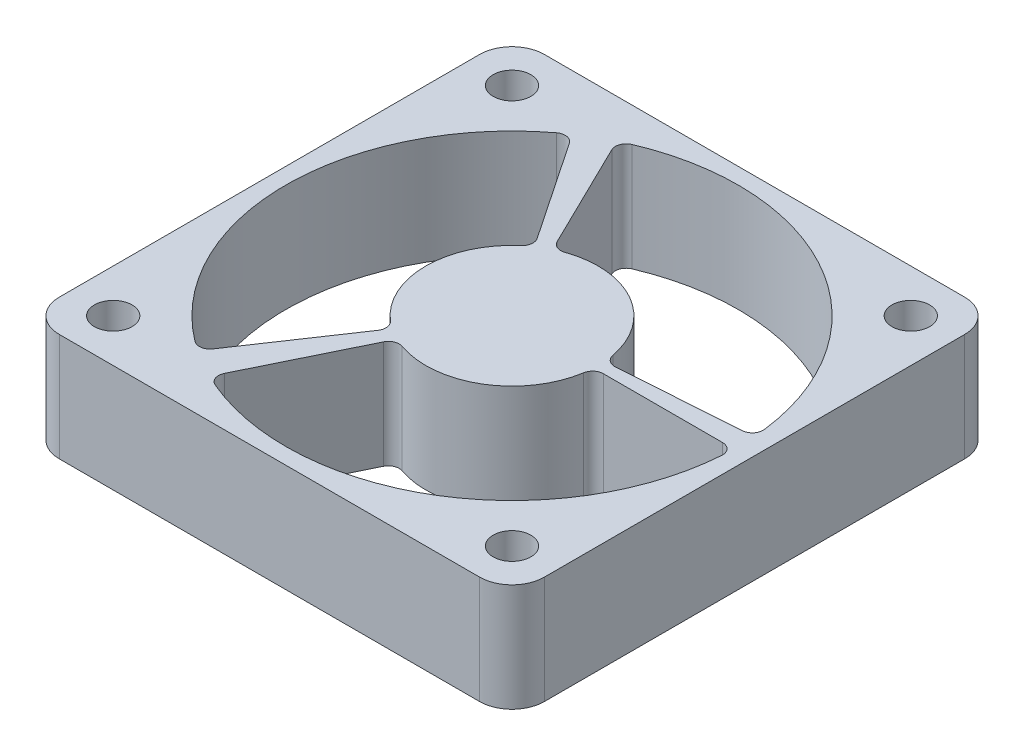
SolidWorks part; units mm, degrees
ref_plane "Płaszczyzna przednia" through (0, 0, 0) normal (0, 0, 1) x (1, 0, 0)
ref_plane "Płaszczyzna górna" through (0, 0, 0) normal (0, 1, 0) x (1, 0, 0)
ref_plane "Płaszczyzna prawa" through (0, 0, 0) normal (1, 0, 0) x (0, 0, -1)
sketch "Szkic1" plane through (0, 0, 0) normal (0, 1, 0) x (1, 0, 0)
  line L1 (19.5, -22.5) -> (-19.5, -22.5)
  line L2 (22.5, -19.5) -> (22.5, 19.5)
  line L3 (19.5, 22.5) -> (-19.5, 22.5)
  line L4 (-22.5, -19.5) -> (-22.5, 19.5)
  line L5 (22.5, -22.5) -> (-22.5, 22.5) construction
  line L6 (22.5, 22.5) -> (-22.5, -22.5) construction
  arc A0 (-19.5, -22.5) -> (-22.5, -19.5) centre (-19.5, -19.5) cw
  arc A1 (19.5, -22.5) -> (22.5, -19.5) centre (19.5, -19.5) ccw
  arc A2 (22.5, 19.5) -> (19.5, 22.5) centre (19.5, 19.5) ccw
  arc A3 (-22.5, 19.5) -> (-19.5, 22.5) centre (-19.5, 19.5) cw
  point P0 (0, 0)
  dimension "D3" = 3
  dimension "D1" = 45
  dimension "D2" = 45
extrude "Dodanie-wyciągnięcie1" add sketch "Szkic1" along normal blind 10
sketch "Szkic2" plane through (0, 10, 0) normal (0, 1, 0) x (1, 0, 0)
  line L0 (19.9498, -0.4161) -> (8.8879, -0.4161)
  line L1 (-22.5, 19.5) -> (-22.5, -19.5) construction
  line L2 (19.5, 22.5) -> (-19.5, 22.5) construction
  line L3 (19.9188, 1.4498) -> (8.9101, 0.6868)
  line L10 (-8.7129, -17.971) -> (-3.8667, -8.0573)
  line L11 (-11.2069, -16.5311) -> (-5.0444, -7.3773)
  line L12 (-11.2069, 16.5311) -> (-5.0444, 7.3773)
  line L13 (-8.7129, 17.971) -> (-3.8667, 8.0573)
  circle A0 centre (-18.5, 18.5) radius 1.75
  circle A1 centre (18.5, 18.5) radius 1.75
  circle A2 centre (18.5, -18.5) radius 1.75
  circle A3 centre (-18.5, -18.5) radius 1.75
  arc A5 (-8.2052, -19.3307) -> (20.9473, -1.4869) centre (0, 0) ccw
  arc A6 (20.8422, 2.5698) -> (-8.2052, 19.3307) centre (0, 0) ccw
  arc A7 (-5.2213, 6.0612) -> (-5.2213, -6.0612) centre (0, 0) ccw
  arc A8 (-12.6382, 16.7713) -> (-12.6382, -16.7713) centre (0, 0) ccw
  arc A9 (-2.6385, -7.5524) -> (7.9004, -1.2587) centre (0, 0) ccw
  arc A10 (7.8586, 1.4973) -> (-2.6385, 7.5524) centre (0, 0) ccw
  arc A11 (-11.2069, 16.5311) -> (-12.6382, 16.7713) centre (-12.0364, 15.9726) ccw
  arc A12 (-12.6382, -16.7713) -> (-11.2069, -16.5311) centre (-12.0364, -15.9726) ccw
  arc A13 (-5.0444, -7.3773) -> (-5.2213, -6.0612) centre (-5.874, -6.8188) ccw
  arc A14 (-5.2213, 6.0612) -> (-5.0444, 7.3773) centre (-5.874, 6.8188) ccw
  arc A15 (-8.7129, -17.971) -> (-8.2052, -19.3307) centre (-7.8145, -18.4102) ccw
  arc A16 (-8.7129, 17.971) -> (-8.2052, 19.3307) centre (-7.8145, 18.4102) cw
  arc A17 (19.9188, 1.4498) -> (20.8422, 2.5698) centre (19.8497, 2.4475) ccw
  arc A18 (7.8586, 1.4973) -> (8.9101, 0.6868) centre (8.841, 1.6844) ccw
  arc A19 (-3.8667, 8.0573) -> (-2.6385, 7.5524) centre (-2.9683, 8.4964) ccw
  arc A20 (-3.8667, -8.0573) -> (-2.6385, -7.5524) centre (-2.9683, -8.4964) cw
  arc A21 (20.9473, -1.4869) -> (19.9498, -0.4161) centre (19.9498, -1.4161) ccw
  arc A22 (8.8879, -0.4161) -> (7.9004, -1.2587) centre (8.8879, -1.4161) ccw
  point P12 (0, 0)
  dimension "D1" = 4
  dimension "D3" = 1
  dimension "D4" = 1
  dimension "D5" = 3.5
  dimension "D8" = 21
  dimension "D9" = 8
  dimension "D2" = 4
  dimension "D6" = 37
  dimension "D7" = 37
extrude "Wytnij-wyciągnięcie1" cut sketch "Szkic2" against normal blind 10
